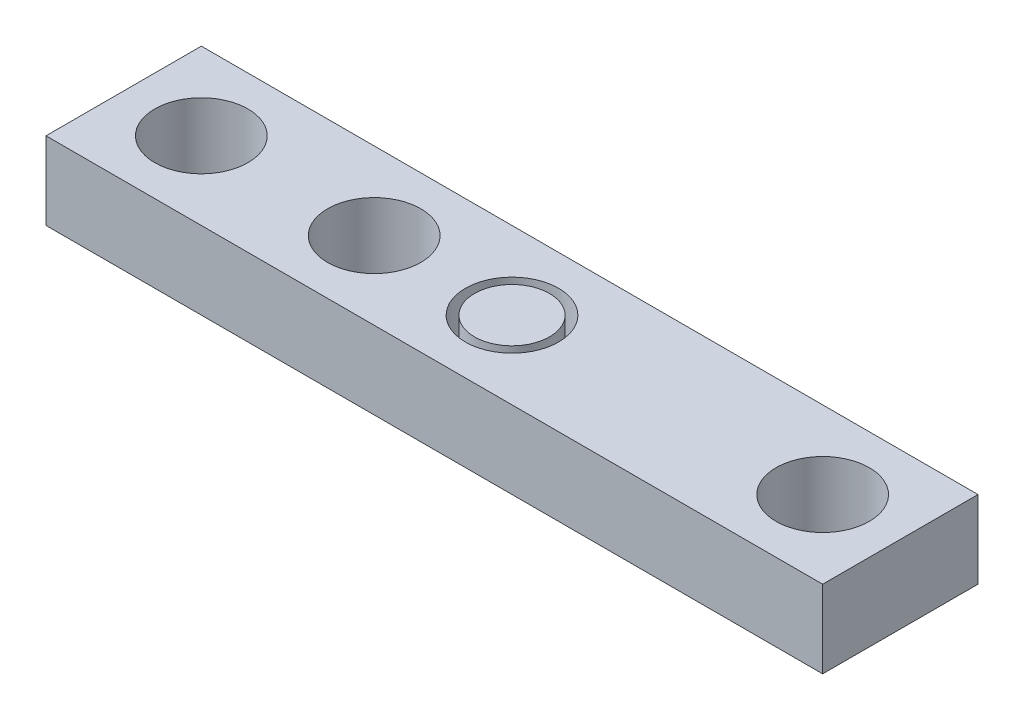
SolidWorks part; units mm, degrees
ref_plane "Front Plane" through (0, 0, 0) normal (0, 0, 1) x (1, 0, 0)
ref_plane "Top Plane" through (0, 0, 0) normal (0, 1, 0) x (1, 0, 0)
ref_plane "Right Plane" through (0, 0, 0) normal (1, 0, 0) x (0, 0, -1)
sketch "Sketch1" plane through (0, 0, 0) normal (0, 1, 0) x (1, 0, 0)
  line L1 (25, 5) -> (-25, 5)
  line L2 (25, 5) -> (25, -5)
  line L3 (25, -5) -> (-25, -5)
  line L4 (-25, 5) -> (-25, -5)
  line L5 (25, 5) -> (-25, -5) construction
  line L6 (25, -5) -> (-25, 5) construction
  circle A0 centre (-20, 0) radius 3
  circle A1 centre (20, 0) radius 3
  point P0 (0, 0)
  dimension "D3" = 6
  dimension "D1" = 10
  dimension "D2" = 50
  dimension "D4" = 5
  dimension "D5" = 5
  dimension "D6" = 40
extrude "Boss-Extrude1" add sketch "Sketch1" along normal mid plane 5
sketch "Sketch2" plane through (0, 2.5, 0) normal (0, 1, 0) x (1, 0, 0)
  circle A0 centre (0, 0) radius 3
extrude "Cut-Extrude1" cut sketch "Sketch2" against normal through all
sketch "Sketch3" plane through (0, 2.5, 0) normal (0, 1, 0) x (1, 0, 0)
  circle A0 centre (-8.8712, 0) radius 3
extrude "Cut-Extrude2" cut sketch "Sketch3" against normal through all
sketch "Sketch4" plane through (0, 2.5, 0) normal (0, 1, 0) x (1, 0, 0)
  circle A0 centre (0, 0) radius 2.4176
extrude "Boss-Extrude3" add sketch "Sketch4" against normal through all separate body
equation "\"D2@Sketch1\"= \"D6@Sketch1\" + 10mm"
